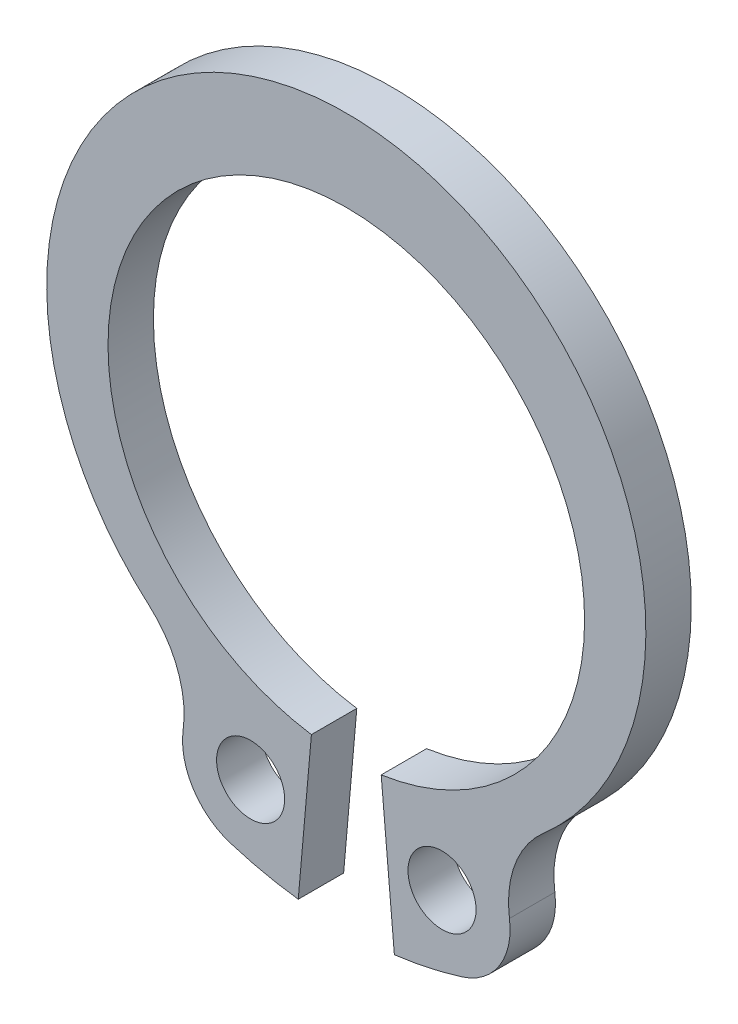
SolidWorks part; units mm, degrees
ref_plane "Face" through (0, 0, 0) normal (0, 0, 1) x (1, 0, 0)
ref_plane "Dessus" through (0, 0, 0) normal (0, 1, 0) x (1, 0, 0)
ref_plane "Droite" through (0, 0, 0) normal (1, 0, 0) x (0, 0, -1)
sketch "Esquisse1" plane through (0, 0, 0) normal (0, 0, 1) x (1, 0, 0)
  line L0 (0, 7.05) -> (0, 5.25) construction
  line L1 (0.7686, -5.1934) -> (1.0589, -8.4806)
  line L2 (-0.7686, -5.1934) -> (-1.0589, -8.4806)
  line L3 (0.3, -5.0912) -> (0.3, -8.3912) construction
  line L4 (-0.3, -5.0912) -> (-0.3, -8.3912) construction
  arc A0 (0.7686, -5.1934) -> (-0.7686, -5.1934) centre (0, 0) ccw
  arc A1 (4.343, -4.5197) -> (-4.343, -4.5197) centre (0, 0.45) ccw
  arc A2 (1.0589, -8.4806) -> (2.5573, -8.1549) centre (0, 0) ccw
  circle A3 centre (2.1084, -6.7237) radius 0.75
  arc A4 (2.5573, -8.1549) -> (3.5945, -6.5198) centre (2.1084, -6.7237) ccw
  arc A5 (4.343, -4.5197) -> (3.5945, -6.5198) centre (5.8236, -6.2139) ccw
  circle A6 centre (-2.1084, -6.7237) radius 0.75
  arc A7 (-4.343, -4.5197) -> (-3.5945, -6.5198) centre (-5.8236, -6.2139) cw
  arc A8 (-2.5573, -8.1549) -> (-3.5945, -6.5198) centre (-2.1084, -6.7237) cw
  arc A9 (-1.0589, -8.4806) -> (-2.5573, -8.1549) centre (0, 0) cw
  arc A10 (0.3, -5.0912) -> (-0.3, -5.0912) centre (0, 0) ccw construction
  circle A11 centre (0, 0) radius 5.5 construction
  dimension "dgorge" = 10.5
  dimension "D3" = 0.45
  dimension "dtrou" = 1.5
  dimension "D8" = 1.5
  dimension "D9" = 2.25
  dimension "dint" = 10.2
  dimension "dn" = 11
  dimension "b" = 1.8
  dimension "a" = 3.3
  dimension "D5" = 16.838
  dimension "D7" = 1.2
  dimension "D12" = 0.6
  dimension "D13" = 6.745
  dimension "D14" = 5.047
extrude "Base-Extrusion" add sketch "Esquisse1" along normal blind 1
equation "\"D3@Esquisse1\" = \"b@Esquisse1\"/4"
equation "\"D7@Esquisse1\"=\"dtrou@Esquisse1\"*0.8"
equation "\"D8@Esquisse1\" = \"dtrou@Esquisse1\""
equation "\"D9@Esquisse1\" = \"dtrou@Esquisse1\"*1.5"
equation "\"D12@Esquisse1\" = \"dtrou@Esquisse1\"*0.4"
equation "\"D5@Esquisse1\" = 360-(360-\"D13@Esquisse1\")*\"dint@Esquisse1\"/\"dgorge@Esquisse1\""
equation "\"D14@Esquisse1\" = (\"D5@Esquisse1\"-\"D13@Esquisse1\")/2"
